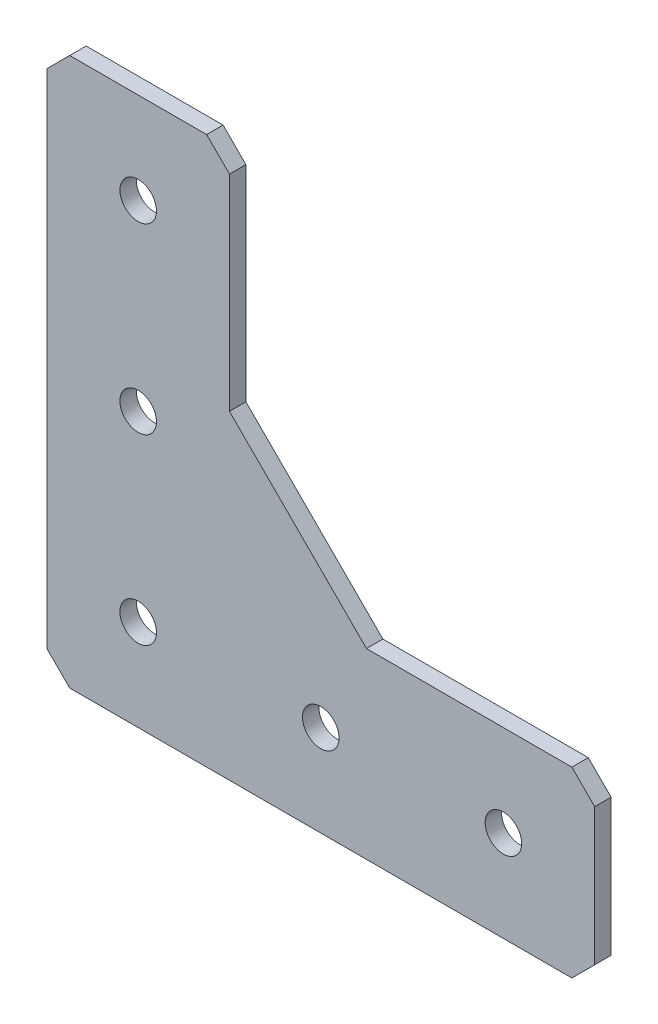
SolidWorks part; units mm, degrees
material "5052-H32"
ref_plane "Front Plane" through (0, 0, 0) normal (0, 0, 1) x (1, 0, 0)
ref_plane "Top Plane" through (0, 0, 0) normal (0, 1, 0) x (1, 0, 0)
ref_plane "Right Plane" through (0, 0, 0) normal (1, 0, 0) x (0, 0, -1)
ref_plane "Plane1" through (0, 0, 0) normal (0, 0, -1) x (-1, 0, 0)
sketch "Sketch1" plane through (0, 0, 0) normal (0, 0, -1) x (-1, 0, 0)
  line L0 (-73.025, 25.4) -> (-76.2, 22.225)
  line L1 (-76.2, 22.225) -> (-76.2, 3.175)
  line L2 (-76.2, 3.175) -> (-73.025, 0)
  line L3 (-73.025, 0) -> (-3.175, 0)
  line L4 (-3.175, 0) -> (0, 3.175)
  line L5 (0, 3.175) -> (0, 73.025)
  line L6 (0, 73.025) -> (-3.175, 76.2)
  line L7 (-3.175, 76.2) -> (-22.225, 76.2)
  line L8 (-22.225, 76.2) -> (-25.4, 73.025)
  line L9 (-25.4, 73.025) -> (-25.4, 44.45)
  line L10 (-25.4, 44.45) -> (-44.45, 25.4)
  line L11 (-44.45, 25.4) -> (-73.025, 25.4)
  circle A0 centre (-12.7, 12.7) radius 2.54
  circle A1 centre (-12.7, 63.5) radius 2.54
  circle A2 centre (-12.7, 38.1) radius 2.54
  circle A3 centre (-63.5, 12.7) radius 2.54
  circle A4 centre (-38.1, 12.7) radius 2.54
extrude "Boss-Extrude1" add sketch "Sketch1" against normal blind 2.286
sketch "Sketch2" [suppressed] plane through (0, 0, 2.286) normal (0, 0, 1) x (1, 0, 0)
  line L0 (25.4, 44.45) -> (25.4, 20.4533) construction
  line L1 (44.45, 25.4) -> (22.4799, 25.4) construction
  line L3 (25.4, 25.4) -> (44.45, 25.4)
  line L4 (25.4, 25.4) -> (25.4, 44.45)
  line L5 (25.4, 44.45) -> (44.45, 44.45)
  line L6 (44.45, 25.4) -> (44.45, 44.45)
extrude "Cut-Extrude1" [suppressed] cut sketch "Sketch2" against normal through all
sketch "Sketch4" [suppressed] plane through (0, 0, 6.35) normal (0, 0, 1) x (1, 0, 0)
  circle A0 centre (12.7, 63.5) radius 3.175
  circle A1 centre (34.2369, 34.5359) radius 3.175
  dimension "D1" = 6.35
  dimension "D2" = 6.35
  dimension "D3" = 8.8369
  dimension "D4" = 9.1359
extrude "Cut-Extrude3" [suppressed] cut sketch "Sketch4" against normal through all
sketch "Sketch5" plane through (0, 0, 2.286) normal (0, 0, 1) x (1, 0, 0)
  line L0 (12.7, 76.2) -> (25.4, 58.7375)
  line L1 (3.175, 76.2) -> (22.225, 76.2) construction
  line L2 (25.4, 58.7375) -> (25.4, 76.2)
  line L3 (25.4, 76.2) -> (12.7, 76.2)
  line L4 (25.4, 73.025) -> (25.4, 44.45) construction
extrude "Cut-Extrude4" [suppressed] cut sketch "Sketch5" against normal through all
sketch "Sketch6" [suppressed] plane through (0, 0, 6.35) normal (0, 0, 1) x (1, 0, 0)
  line L0 (25.4, 58.7375) -> (73.025, 25.4)
  line L1 (25.4, 58.7375) -> (25.4, 44.45)
  line L2 (25.4, 44.45) -> (32.596, 37.254)
  line L3 (36.955, 32.895) -> (44.45, 25.4) construction
  line L4 (44.45, 25.4) -> (73.025, 25.4) construction
  line L5 (36.955, 32.895) -> (44.45, 25.4)
  line L6 (44.45, 25.4) -> (73.025, 25.4)
  arc A0 (32.596, 37.254) -> (36.955, 32.895) centre (34.2369, 34.5359) ccw construction
  arc A1 (32.596, 37.254) -> (36.955, 32.895) centre (34.2369, 34.5359) ccw
extrude "Boss-Extrude2" [suppressed] add sketch "Sketch6" against normal blind 6.35
sketch "Sketch7" [suppressed] plane through (0, 0, 6.35) normal (0, 0, 1) x (1, 0, 0)
  line L0 (73.025, 0) -> (3.175, 0) construction
  line L1 (0, 3.175) -> (0, 73.025) construction
  circle A0 centre (34.2369, 34.7254) radius 3.2962
  dimension "D1" = 34.7254
  dimension "D2" = 34.2369
extrude "Cut-Extrude5" [suppressed] cut sketch "Sketch7" against normal through all
